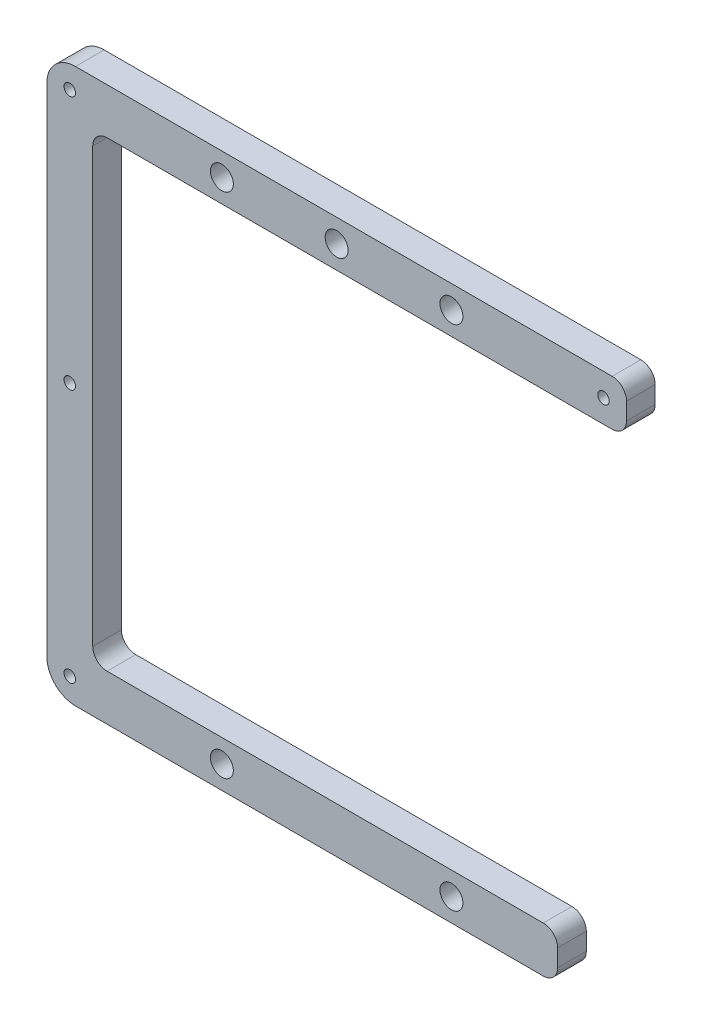
SolidWorks part; units mm, degrees
ref_plane "Front Plane" through (0, 0, 0) normal (0, 0, 1) x (1, 0, 0)
ref_plane "Top Plane" through (0, 0, 0) normal (0, 1, 0) x (1, 0, 0)
ref_plane "Right Plane" through (0, 0, 0) normal (1, 0, 0) x (0, 0, -1)
sketch "Sketch1" plane through (0, 0, 0) normal (0, 0, 1) x (1, 0, 0)
  line L0 (0, -43.25) -> (0, 43.25)
  line L1 (5, 48.25) -> (98.5, 48.25)
  line L2 (101, 45.75) -> (101, 42.75)
  line L3 (98.5, 40.25) -> (10.5, 40.25)
  line L4 (8, 37.75) -> (8, -37.75)
  line L5 (10.5, -40.25) -> (86.5, -40.25)
  line L7 (86.5, -48.25) -> (5, -48.25)
  line L8 (89, -42.75) -> (89, -45.75)
  arc A0 (0, -43.25) -> (5, -48.25) centre (5, -43.25) ccw
  arc A1 (0, 43.25) -> (5, 48.25) centre (5, 43.25) cw
  arc A2 (101, 42.75) -> (98.5, 40.25) centre (98.5, 42.75) cw
  arc A3 (98.5, 48.25) -> (101, 45.75) centre (98.5, 45.75) cw
  arc A6 (8, -37.75) -> (10.5, -40.25) centre (10.5, -37.75) ccw
  arc A7 (10.5, 40.25) -> (8, 37.75) centre (10.5, 37.75) ccw
  arc A8 (89, -45.75) -> (86.5, -48.25) centre (86.5, -45.75) cw
  arc A9 (89, -42.75) -> (86.5, -40.25) centre (86.5, -42.75) ccw
  point P4 (0, 0)
  dimension "D6" = 5
  dimension "D7" = 2.5
  dimension "D9" = 2.5
  dimension "D1" = 88.5
  dimension "D2" = 8
  dimension "D3" = 8
  dimension "D4" = 8
  dimension "D5" = 101
  dimension "D8" = 12
extrude "Boss-Extrude1" add sketch "Sketch1" along normal blind 5
sketch "Sketch4" plane through (0, 0, 5) normal (0, 0, 1) x (1, 0, 0)
  line L0 (50.5, 52.0993) -> (50.5, -52.0993) construction
  line L1 (0, 43.25) -> (0, -43.25) construction
  line L2 (101, 42.75) -> (101, 45.75) construction
  line L3 (101, 44.25) -> (10.5, 44.25) construction
  line L4 (0, 0) -> (111.1347, 0) construction
  circle A0 centre (70.5, 44.25) radius 2
  circle A1 centre (30.5, 44.25) radius 2
  circle A2 centre (70.5, -44.25) radius 2
  circle A3 centre (30.5, -44.25) radius 2
  circle A4 centre (50.5, 44.25) radius 2
  dimension "D2" = 4
  dimension "D3" = 4
  dimension "D6" = 4
  dimension "D1" = 50.5
  dimension "D4" = 20
  dimension "D5" = 20
extrude "Cut-Extrude1" cut sketch "Sketch4" against normal through all
sketch "Sketch5" plane through (0, 0, 5) normal (0, 0, 1) x (1, 0, 0)
  line L0 (101, 44.25) -> (-12.5105, 44.25) construction
  line L1 (101, 42.75) -> (101, 45.75) construction
  line L2 (89, -44.25) -> (-12.5105, -44.25) construction
  line L3 (89, -45.75) -> (89, -42.75) construction
  line L4 (4, 53.2514) -> (4, -51.7153) construction
  circle A0 centre (4, 44.25) radius 1
  circle A1 centre (4, 0) radius 1
  circle A2 centre (4, -44.25) radius 1
  circle A3 centre (97, 44.25) radius 1
  dimension "D2" = 2
  dimension "D3" = 2
  dimension "D4" = 2
  dimension "D5" = 2
  dimension "D1" = 4
  dimension "D6" = 93
extrude "Cut-Extrude2" cut sketch "Sketch5" against normal blind 3
equation "\"38.5mmmm\"=27.8036"
